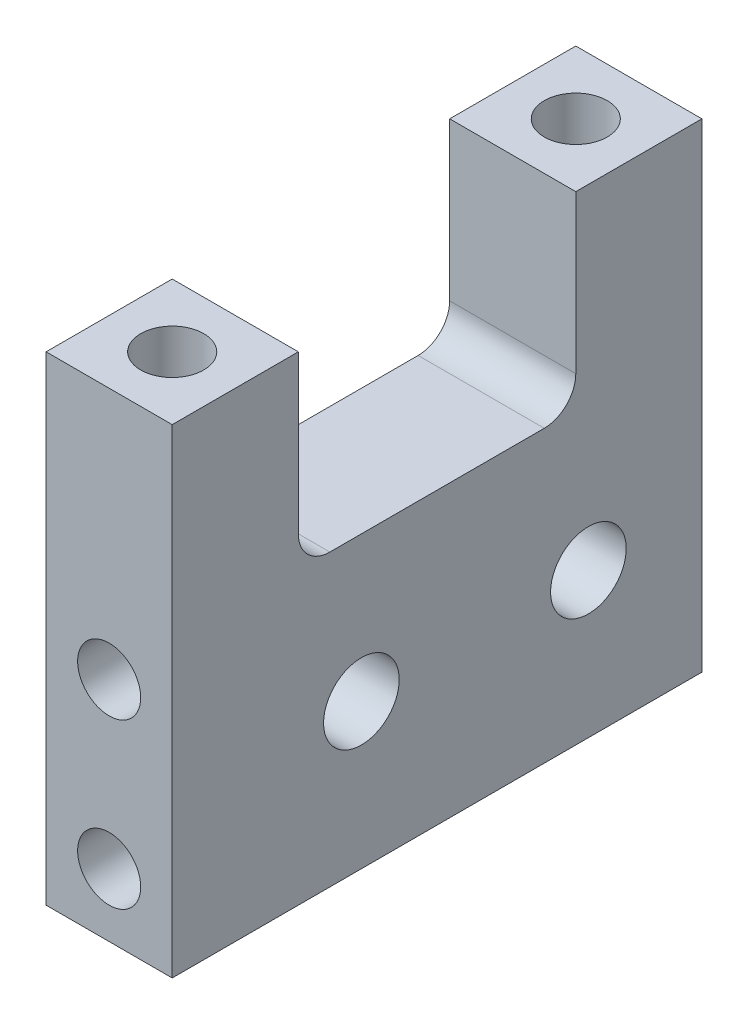
SolidWorks part; units mm, degrees
ref_plane "Plan de face" through (0, 0, 0) normal (0, 0, 1) x (1, 0, 0)
ref_plane "Plan de dessus" through (0, 0, 0) normal (0, 1, 0) x (1, 0, 0)
ref_plane "Plan de droite" through (0, 0, 0) normal (1, 0, 0) x (0, 0, -1)
sketch "Esquisse1" plane through (0, 0, 0) normal (1, 0, 0) x (0, 0, -1)
  line L1 (0, 0) -> (42, 0)
  line L2 (0, 0) -> (0, 38)
  line L3 (0, 38) -> (42, 38)
  line L4 (42, 0) -> (42, 38)
  dimension "D1" = 42
  dimension "D2" = 38
extrude "Extrusion1" add sketch "Esquisse1" along normal blind 10
sketch "Esquisse2" plane through (0, 0, 0) normal (0, 0, 1) x (1, 0, 0)
  line L0 (0, 38) -> (0, 0) construction
  line L1 (10, 0) -> (0, 0) construction
  line L2 (10, 38) -> (0, 38) construction
  circle A0 centre (5, 5) radius 2.5
  circle A1 centre (5, 18) radius 2.5
  dimension "D1" = 5
  dimension "D3" = 5
  dimension "D4" = 5
  dimension "D5" = 20
  dimension "D2" = 5
extrude "Extrusion3" cut sketch "Esquisse2" against normal through all
sketch "Esquisse4" plane through (0, 38, 0) normal (0, 1, 0) x (1, 0, 0)
  line L0 (0, 42) -> (0, 0) construction
  line L1 (10, 0) -> (0, 0) construction
  line L2 (10, 42) -> (0, 42) construction
  circle A0 centre (5, 5) radius 2.5
  circle A1 centre (5, 37) radius 2.5
  dimension "D1" = 5
  dimension "D2" = 5
  dimension "D3" = 5
  dimension "D6" = 5
  dimension "D4" = 5
  dimension "D5" = 5
extrude "Extrusion4" cut sketch "Esquisse4" against normal up to next
sketch "Esquisse5" plane through (0, 0, 0) normal (-1, 0, 0) x (0, 0, 1)
  line L0 (-42, 0) -> (-42, 38) construction
  line L1 (-32, 40.063) -> (-10, 40.063)
  line L2 (-32, 40.063) -> (-32, 25.5)
  line L3 (-29.5, 23) -> (-12.5, 23)
  line L4 (-10, 40.063) -> (-10, 25.5)
  line L5 (0, 38) -> (0, 0) construction
  line L6 (-42, 38) -> (0, 38) construction
  arc A0 (-32, 25.5) -> (-29.5, 23) centre (-29.5, 25.5) ccw
  arc A1 (-12.5, 23) -> (-10, 25.5) centre (-12.5, 25.5) ccw
  dimension "D4" = 5
  dimension "D5" = 5
  dimension "D1" = 10
  dimension "D2" = 10
  dimension "D3" = 15
extrude "Extrusion5" cut sketch "Esquisse5" against normal through all
sketch "Esquisse6" plane through (0, 0, 0) normal (-1, 0, 0) x (0, 0, 1)
  line L0 (0, 0) -> (-42, 0) construction
  line L1 (-42, 0) -> (-42, 38) construction
  circle A0 centre (-33, 11.5) radius 3
  circle A1 centre (-15, 11.5) radius 3
  dimension "D1" = 6
  dimension "D2" = 6
  dimension "D3" = 11.5
  dimension "D4" = 11.5
  dimension "D5" = 9
  dimension "D6" = 18
extrude "Extrusion6" cut sketch "Esquisse6" against normal through all
